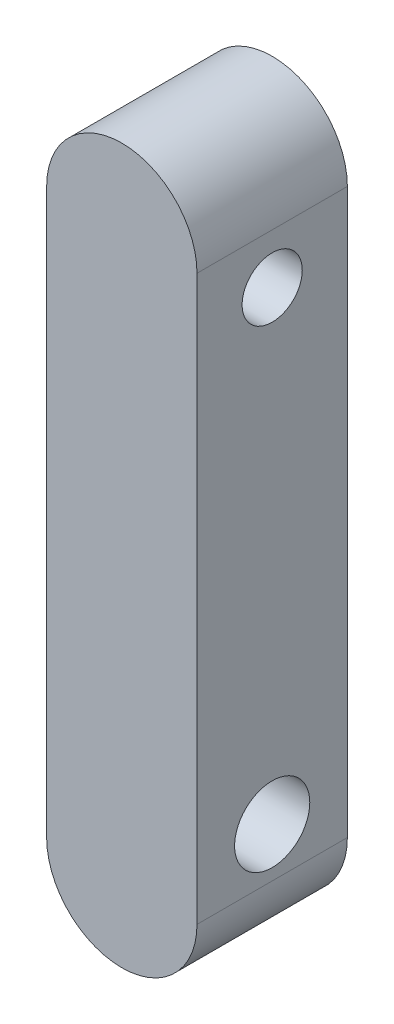
SolidWorks part; units mm, degrees
ref_plane "Front Plane" through (0, 0, 0) normal (0, 0, 1) x (1, 0, 0)
ref_plane "Top Plane" through (0, 0, 0) normal (0, 1, 0) x (1, 0, 0)
ref_plane "Right Plane" through (0, 0, 0) normal (1, 0, 0) x (0, 0, -1)
sketch "Sketch2" plane through (0, 0, 0) normal (0, 0, 1) x (1, 0, 0)
  line L0 (0, 0) -> (0, 75) construction
  line L1 (-10, 0) -> (-10, 75)
  line L2 (10, 0) -> (10, 75)
  arc A0 (-10, 0) -> (10, 0) centre (0, 0) ccw
  arc A1 (10, 75) -> (-10, 75) centre (0, 75) ccw
  circle A2 centre (0, 0) radius 5
  point P2 (0, 37.5)
  dimension "D1" = 20
  dimension "D2" = 75
extrude "Boss-Extrude1" add sketch "Sketch2" along normal blind 20
sketch "Sketch4" plane through (10, 0, 0) normal (1, 0, 0) x (0, 0, -1)
  line L0 (-10, 75) -> (-10, 68.36) construction
  line L1 (-20, 75) -> (0, 75) construction
  circle A0 centre (-10, 68.36) radius 4
  dimension "D2" = 8
  dimension "D1" = 6.64
extrude "Cut-Extrude1" cut sketch "Sketch4" against normal blind 28
sketch "Sketch5" plane through (10, 0, 0) normal (1, 0, 0) x (0, 0, -1)
  line L0 (-10, 0) -> (-10, 6.54) construction
  line L1 (-20, 0) -> (0, 0) construction
  circle A0 centre (-10, 6.54) radius 5
  dimension "D1" = 6.54
extrude "Cut-Extrude2" cut sketch "Sketch5" against normal blind 30
ref_plane "Plane5" through (20, 0, 0) normal (1, 0, 0) x (0, 0, -1)
sketch "Sketch11" plane through (20, 0, 0) normal (1, 0, 0) x (0, 0, -1)
  line L0 (-10, 99.513) -> (-10, 50.487) construction
  line L2 (16.1409, 68.36) -> (-36.1409, 68.36) construction
  point P3 (-10, 75)
  point P7 (-10, 68.36)
sketch "Sketch12" plane through (0, 0, 20) normal (0, 0, 1) x (1, 0, 0)
  circle A0 centre (0, 0) radius 5
extrude "Boss-Extrude2" add sketch "Sketch12" against normal blind 20
sketch "Sketch13" plane through (10, 0, 0) normal (1, 0, 0) x (0, 0, -1)
  line L0 (-10, 11.54) -> (-10, 1.54) construction
  line L1 (-15, 6.54) -> (-10, 6.54) construction
  line L2 (-10, 6.54) -> (-5, 6.54) construction
  circle A0 centre (-10, 6.54) radius 5
  point P4 (-10, 6.54)
  dimension "D1" = 10
  dimension "D2" = 61.82
extrude "Cut-Extrude3" cut sketch "Sketch13" against normal blind 20
ref_plane "Plane6" through (0, 68.36, 0) normal (0, 1, 0) x (1, 0, 0)
sketch "Sketch14" plane through (0, 68.36, 0) normal (0, 1, 0) x (1, 0, 0)
  line L0 (0, 0) -> (0, -20) construction
  line L1 (-10, -20) -> (10, -20) construction
  line L2 (20.8285, -10) -> (-20.8285, -10) construction
  point P8 (0, -10)
